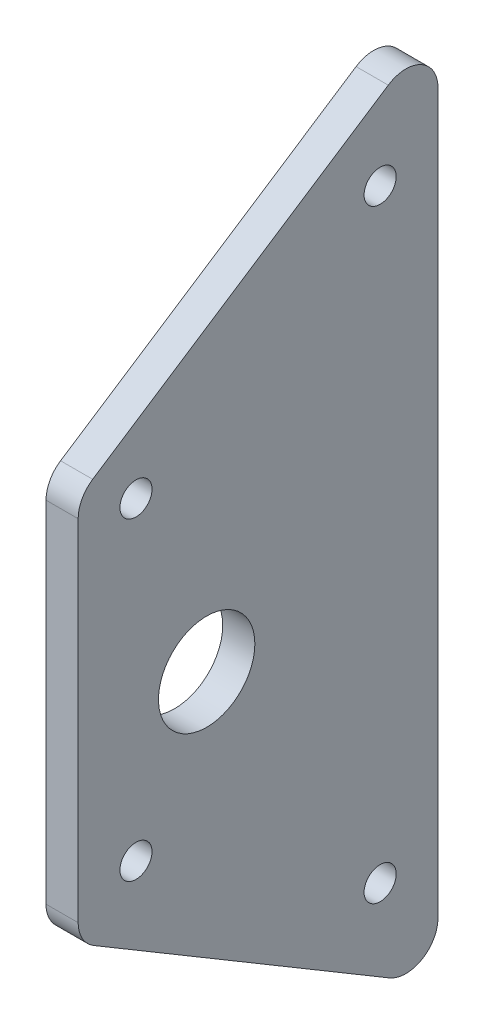
SolidWorks part; units mm, degrees
ref_plane "Front Plane" through (0, 0, 0) normal (0, 0, 1) x (1, 0, 0)
ref_plane "Top Plane" through (0, 0, 0) normal (0, 1, 0) x (1, 0, 0)
ref_plane "Right Plane" through (0, 0, 0) normal (1, 0, 0) x (0, 0, -1)
sketch "Sketch1" plane through (0, 0, 0) normal (1, 0, 0) x (0, 0, -1)
  line L0 (-52.6447, 31.005) -> (-52.6447, -45.195)
  line L1 (-52.6447, -45.195) -> (18.4753, -87.5094)
  line L2 (18.4753, -87.5094) -> (18.4753, 77.5906)
  line L3 (18.4753, 77.5906) -> (-52.6447, 31.005)
  line L4 (18.4753, 77.5906) -> (-52.6447, 77.5906) construction
  line L5 (18.4753, -87.5094) -> (-62.6235, -87.5094) construction
  circle A0 centre (7.0453, 54.7306) radius 3.175
  circle A1 centre (-41.2147, 25.3333) radius 3.175
  circle A2 centre (7.0453, -64.6494) radius 3.175
  circle A3 centre (-41.2147, -36.7094) radius 3.175
  circle A4 centre (-27.2447, -11.3094) radius 9.525
  dimension "D4" = 6.35
  dimension "D5" = 6.35
  dimension "D6" = 6.35
  dimension "D7" = 6.35
  dimension "D8" = 19.05
  dimension "D1" = 71.12
  dimension "D2" = 76.2
  dimension "D3" = 165.1
  dimension "D9" = 11.43
  dimension "D10" = 52.2573
  dimension "D11" = 11.43
  dimension "D12" = 50.8
  dimension "D13" = 11.43
  dimension "D14" = 11.43
  dimension "D15" = 25.4
  dimension "D16" = 76.2
extrude "Boss-Extrude1" add sketch "Sketch1" along normal blind 6.35
fillet "Fillet1" radius 6.35 4 edges at (3.175, 77.5906, -18.4753) (3.175, 31.005, 52.6447) (3.175, -45.195, 52.6447) (3.175, -87.5094, -18.4753)
ref_plane "Plane2" through (0, 0, 0) normal (-1, 0, 0) x (0, 0, 1)
sketch "Sketch3" plane through (0, 0, 0) normal (-1, 0, 0) x (0, 0, 1)
  circle A0 centre (-7.0453, 54.7306) radius 6.35
  circle A1 centre (41.2147, 25.3333) radius 6.35
  circle A2 centre (41.2147, -36.7094) radius 6.35
  circle A3 centre (-7.0453, -64.6494) radius 6.35
  circle A4 centre (-7.0453, 54.7306) radius 3.175
  dimension "D1" = 12.7
  dimension "D2" = 12.7
  dimension "D3" = 12.7
  dimension "D4" = 12.7
extrude "Cut-Extrude1" cut sketch "Sketch3" against normal blind 1.27
